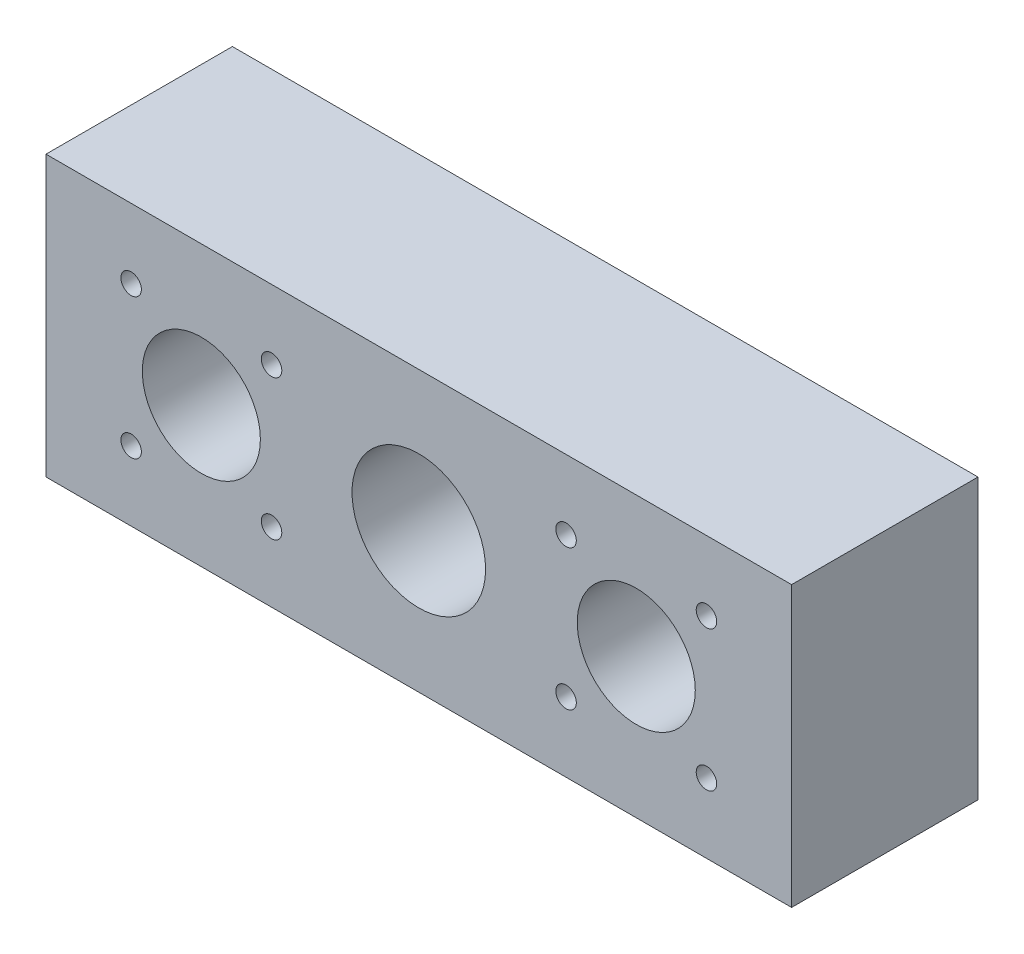
SolidWorks part; units mm, degrees
ref_plane "前视基准面" through (0, 0, 0) normal (0, 0, 1) x (1, 0, 0)
ref_plane "上视基准面" through (0, 0, 0) normal (0, 1, 0) x (1, 0, 0)
ref_plane "右视基准面" through (0, 0, 0) normal (1, 0, 0) x (0, 0, -1)
sketch "草图1" plane through (0, 0, 0) normal (0, 0, 1) x (1, 0, 0)
  line L1 (-60, -22.5) -> (60, -22.5)
  line L2 (-60, -22.5) -> (-60, 22.5)
  line L3 (-60, 22.5) -> (60, 22.5)
  line L4 (60, -22.5) -> (60, 22.5)
  line L5 (-60, -22.5) -> (60, 22.5) construction
  line L6 (-60, 22.5) -> (60, -22.5) construction
  point P0 (0, 0)
  dimension "D1" = 120
  dimension "D2" = 45
extrude "凸台-拉伸1" add sketch "草图1" along normal blind 30
sketch "草图2" plane through (0, 0, 30) normal (0, 0, 1) x (1, 0, 0)
  line L0 (0, 22.5) -> (0, -22.5) construction
  line L1 (60, 22.5) -> (-60, 22.5) construction
  line L2 (-60, -22.5) -> (60, -22.5) construction
  line L3 (-60, 0) -> (60, 0) construction
  line L4 (-60, 22.5) -> (-60, -22.5) construction
  line L5 (60, -22.5) -> (60, 22.5) construction
  circle A0 centre (-35, 0) radius 9.5
  circle A1 centre (35, 0) radius 9.5
  circle A2 centre (0, 0) radius 10.75
  dimension "D1" = 70
  dimension "D2" = 19
  dimension "D3" = 21.5
extrude "切除-拉伸1" cut sketch "草图2" against normal up to next
hole_wizard "M4 螺纹孔1" positions "草图4" profile "草图5" tap size "M4" standard "Iso"
sketch "草图4" plane through (0, 0, 30) normal (0, 0, 1) x (1, 0, 0)
  line L0 (-35, 22.5) -> (-35, -22.5) construction
  line L1 (60, 22.5) -> (-60, 22.5) construction
  line L2 (-60, -22.5) -> (60, -22.5) construction
  line L5 (-46.3, -11.3) -> (-23.7, -11.3)
  line L6 (-46.3, -11.3) -> (-46.3, 11.3)
  line L7 (-46.3, 11.3) -> (-23.7, 11.3)
  line L8 (-23.7, -11.3) -> (-23.7, 11.3)
  line L9 (-46.3, -11.3) -> (-23.7, 11.3) construction
  line L10 (-46.3, 11.3) -> (-23.7, -11.3) construction
  line L11 (0, 22.5) -> (0, -22.5) construction
  point P10 (-35, 0)
  point P11 (-23.7, 11.3)
  point P54 (-46.3, -11.3)
  point P55 (-46.3, 11.3)
  point P56 (-23.7, -11.3)
  point P73 (46.3, 11.3)
  point P74 (46.3, -11.3)
  point P75 (23.7, -11.3)
  point P76 (23.7, 11.3)
  dimension "D1" = 22.6
  dimension "D2" = 22.6
sketch "草图5" plane through (23.7, 11.3, 30) normal (1, 0, 0) x (0, -1, 0)
  line L0 (0, 0) -> (0, 11.0914)
  line L1 (0, 11.0914) -> (1.65, 10.1)
  line L2 (1.65, 10.1) -> (1.65, 0)
  line L5 (1.65, 0) -> (0, 0)
  line L10 (0, 11.0914) -> (-1.65, 10.1) construction
  line L11 (0, -6.35) -> (0, 107.95) construction
  dimension "螺纹孔钻头直径" = 3.3
  dimension "螺纹孔钻头深度" = 10.1
  dimension "导头角度" = 118
cosmetic thread "孔螺蚊线10" parameters "D1"=8, "D2"=4
cosmetic thread "孔螺蚊线11" parameters "D1"=8, "D2"=4
cosmetic thread "孔螺蚊线12" parameters "D1"=8, "D2"=4
cosmetic thread "孔螺蚊线13" parameters "D1"=8, "D2"=4
cosmetic thread "孔螺蚊线14" parameters "D1"=8, "D2"=4
cosmetic thread "孔螺蚊线15" parameters "D1"=8, "D2"=4
cosmetic thread "孔螺蚊线16" parameters "D1"=8, "D2"=4
cosmetic thread "孔螺蚊线17" parameters "D1"=8, "D2"=4
hole_wizard "M4 螺纹孔2" positions "草图16" profile "草图15" tap size "M4" standard "Gb"
sketch "草图16" plane through (0, 0, 0) normal (0, 0, -1) x (-1, 0, 0)
  line L8 (0, 0) -> (-11.3137, 11.3137)
  line L10 (0, 0) -> (16, 0)
  line L12 (0, 0) -> (-11.3137, -11.3137)
  line L14 (0, 0) -> (11.3137, -11.3137)
  line L16 (0, 0) -> (11.3137, 11.3137)
  circle A0 centre (0, 0) radius 16
  point P2 (11.3137, 11.3137)
  point P109 (-11.3137, -11.3137)
  point P110 (-11.3137, 11.3137)
  point P111 (11.3137, -11.3137)
  dimension "D1" = 32
  dimension "D2" = 45
  dimension "D3" = 45
  dimension "D4" = 45
sketch "草图15" plane through (-11.3137, 11.3137, 0) normal (1, 0, 0) x (0, 1, 0)
  line L0 (0, 0) -> (0, 11.0914)
  line L1 (0, 11.0914) -> (1.65, 10.1)
  line L2 (1.65, 10.1) -> (1.65, 0)
  line L5 (1.65, 0) -> (0, 0)
  line L10 (0, 11.0914) -> (-1.65, 10.1) construction
  line L11 (0, -6.35) -> (0, 107.95) construction
  dimension "螺纹孔钻头直径" = 3.3
  dimension "螺纹孔钻头深度" = 10.1
  dimension "导头角度" = 118
cosmetic thread "孔螺蚊线6" parameters "D1"=8, "D2"=4
cosmetic thread "孔螺蚊线7" parameters "D1"=8, "D2"=4
cosmetic thread "孔螺蚊线8" parameters "D1"=8, "D2"=4
cosmetic thread "孔螺蚊线9" parameters "D1"=8, "D2"=4
sketch "草图18" plane through (0, -22.5, 0) normal (0, -1, 0) x (1, 0, 0)
  line L0 (0, 30) -> (0, 0) construction
  line L1 (-60, 30) -> (60, 30) construction
  line L2 (0, 30) -> (-60, 0) construction
  line L3 (-60, 30) -> (0, 0) construction
  line L4 (-40.6066, 25.6066) -> (-19.3934, 25.6066)
  line L5 (-40.6066, 25.6066) -> (-40.6066, 4.3934)
  line L6 (-40.6066, 4.3934) -> (-19.3934, 4.3934)
  line L7 (-19.3934, 25.6066) -> (-19.3934, 4.3934)
  line L8 (-40.6066, 25.6066) -> (-19.3934, 4.3934) construction
  line L9 (-40.6066, 4.3934) -> (-19.3934, 25.6066) construction
  line L10 (40.6066, 4.3934) -> (19.3934, 4.3934)
  line L11 (40.6066, 25.6066) -> (40.6066, 4.3934)
  line L12 (40.6066, 25.6066) -> (19.3934, 25.6066)
  line L13 (19.3934, 25.6066) -> (19.3934, 4.3934)
  circle A0 centre (-30, 15) radius 15
hole_wizard "M3 螺纹孔1" positions "草图21" profile "草图22" tap size "M3" standard "GB"
sketch "草图21" plane through (0, -22.5, 0) normal (0, -1, 0) x (-1, 0, 0)
  point P0 (-40.6066, -4.3934)
  point P3 (-19.3934, -4.3934)
  point P6 (-19.3934, -25.6066)
  point P9 (-40.6066, -25.6066)
  point P12 (19.3934, -4.3934)
  point P15 (40.6066, -4.3934)
  point P18 (19.3934, -25.6066)
  point P21 (40.6066, -25.6066)
sketch "草图22" plane through (40.6066, -22.5, 4.3934) normal (1, 0, 0) x (0, 0, -1)
  line L0 (0, 0) -> (0, 8.2511)
  line L1 (0, 8.2511) -> (1.25, 7.5)
  line L2 (1.25, 7.5) -> (1.25, 0)
  line L5 (1.25, 0) -> (0, 0)
  line L10 (0, 8.2511) -> (-1.25, 7.5) construction
  line L11 (0, -6.35) -> (0, 107.95) construction
  dimension "螺纹孔钻头直径" = 2.5
  dimension "螺纹孔钻头深度" = 7.5
  dimension "导头角度" = 118
cosmetic thread "孔螺蚊线18" parameters "D1"=6, "D2"=3
cosmetic thread "孔螺蚊线19" parameters "D1"=6, "D2"=3
cosmetic thread "孔螺蚊线20" parameters "D1"=6, "D2"=3
cosmetic thread "孔螺蚊线21" parameters "D1"=6, "D2"=3
cosmetic thread "孔螺蚊线22" parameters "D1"=6, "D2"=3
cosmetic thread "孔螺蚊线23" parameters "D1"=6, "D2"=3
cosmetic thread "孔螺蚊线24" parameters "D1"=6, "D2"=3
cosmetic thread "孔螺蚊线25" parameters "D1"=6, "D2"=3
